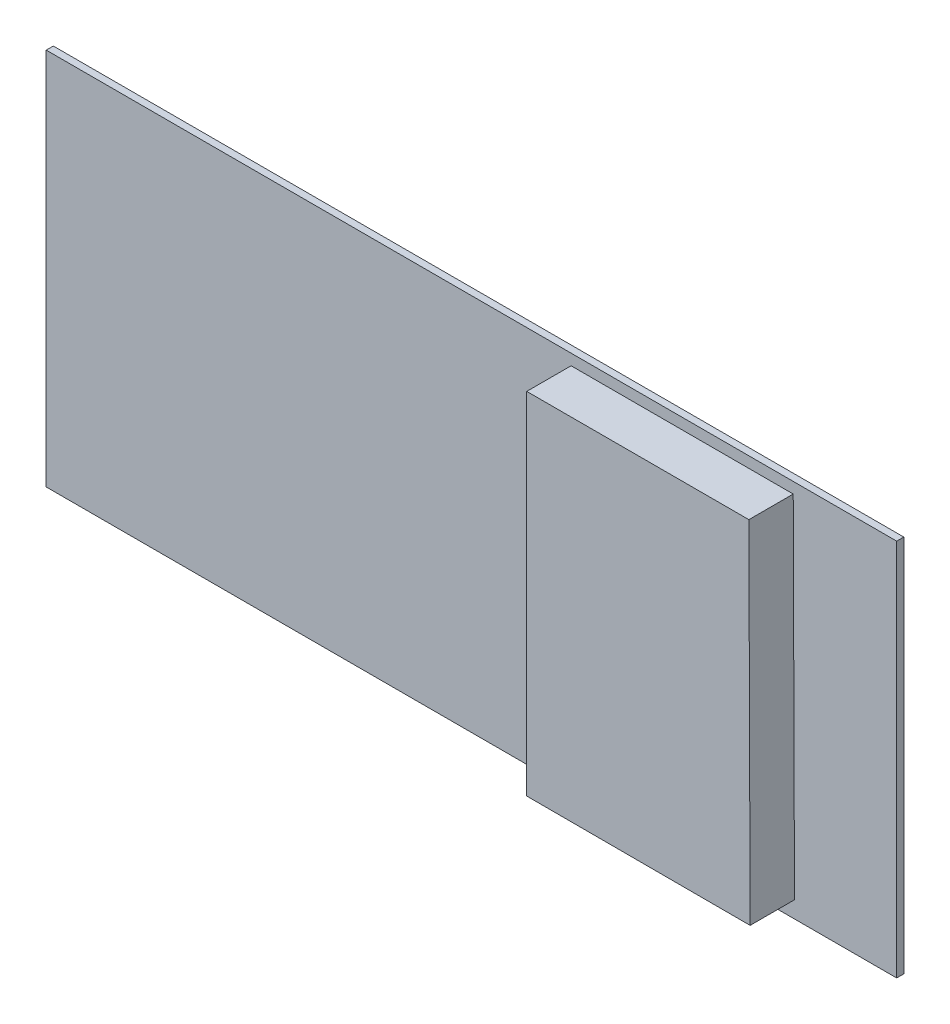
SolidWorks part; units mm, degrees
ref_plane "Front Plane" through (0, 0, 0) normal (0, 0, 1) x (1, 0, 0)
ref_plane "Top Plane" through (0, 0, 0) normal (0, 1, 0) x (1, 0, 0)
ref_plane "Right Plane" through (0, 0, 0) normal (1, 0, 0) x (0, 0, -1)
sketch "Sketch1" plane through (0, 0, 0) normal (0, 0, 1) x (1, 0, 0)
  line L0 (78.5, 146.1) -> (212.7, 146.1) construction
  line L1 (78.5, 86.4) -> (78.5, 146.1) construction
  line L2 (212.7, 86.4) -> (78.5, 86.4) construction
  line L3 (212.7, 146.1) -> (212.7, 86.4) construction
  line L4 (78.5, 146.1) -> (212.7, 146.1)
  line L5 (78.5, 86.4) -> (78.5, 146.1)
  line L6 (212.7, 86.4) -> (78.5, 86.4)
  line L7 (212.7, 146.1) -> (212.7, 86.4)
  line L8 (196.5745, 89.0255) -> (179.4255, 89.0255) construction
  line L9 (196.5745, 106.1745) -> (196.5745, 89.0255) construction
  line L10 (196.3745, 144.3745) -> (196.3745, 127.2255) construction
  line L11 (179.2255, 144.3745) -> (196.3745, 144.3745) construction
  line L12 (161.2255, 127.2255) -> (161.2255, 144.3745) construction
  line L13 (161.2255, 144.3745) -> (178.3745, 144.3745) construction
  line L14 (178.4745, 89.073) -> (161.3255, 89.073) construction
  line L15 (161.3255, 89.073) -> (161.3255, 106.222) construction
  line L16 (196.5745, 89.0255) -> (179.4255, 89.0255)
  line L17 (196.5745, 106.1745) -> (196.5745, 89.0255)
  line L18 (196.3745, 144.3745) -> (196.3745, 127.2255)
  line L19 (179.2255, 144.3745) -> (196.3745, 144.3745)
  line L20 (161.2255, 127.2255) -> (161.2255, 144.3745)
  line L21 (161.2255, 144.3745) -> (178.3745, 144.3745)
  line L22 (178.4745, 89.073) -> (161.3255, 89.073)
  line L23 (161.3255, 89.073) -> (161.3255, 106.222)
extrude "Boss-Extrude1" add sketch "Sketch1" along normal blind 1.12
sketch "Sketch2" plane through (0, 0, 1.12) normal (0, 0, 1) x (1, 0, 0)
  line L1 (161.3255, 89.073) -> (161.3255, 106.222) construction
  line L4 (161.3255, 89.073) -> (196.5745, 89.0255)
  line L5 (196.3745, 144.3745) -> (196.5745, 89.0255)
  line L6 (161.3255, 144.3745) -> (196.3745, 144.3745)
  line L17 (161.3255, 89.073) -> (161.3255, 144.3745)
extrude "Boss-Extrude2" add sketch "Sketch2" along normal blind 7
